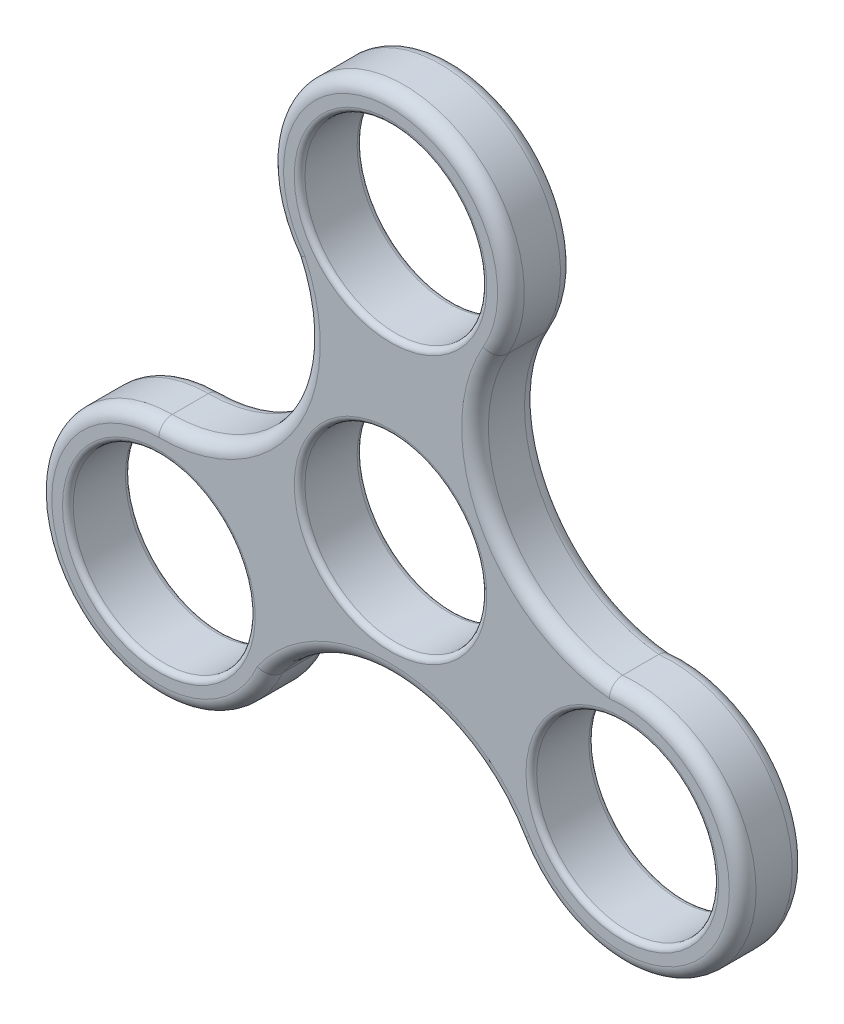
SolidWorks part; units mm, degrees
material "AISI 1020"
ref_plane "Front Plane" through (0, 0, 0) normal (0, 0, 1) x (1, 0, 0)
ref_plane "Top Plane" through (0, 0, 0) normal (0, 1, 0) x (1, 0, 0)
ref_plane "Right Plane" through (0, 0, 0) normal (1, 0, 0) x (0, 0, -1)
sketch "Sketch1" plane through (0, 0, 0) normal (0, 0, 1) x (1, 0, 0)
  line L0 (0, 434.2746) -> (0, -347.9459) construction
  line L1 (-480.6623, 0) -> (486.6372, 0) construction
  line L2 (251.1474, -145) -> (95.2628, -55) construction
  line L3 (-251.1474, -145) -> (-95.2628, -55) construction
  line L4 (-58.8897, -34) -> (58.8897, 34) construction
  line L5 (58.8897, -34) -> (-58.8897, 34) construction
  line L6 (376.0928, -217.1373) -> (-301.33, 173.9729) construction
  line L7 (-376.0928, -217.1373) -> (301.33, 173.9729) construction
  circle A0 centre (0, 0) radius 68
  arc A1 (77.9423, 155) -> (-72.6038, 146.8146) centre (0, 200) ccw
  arc A2 (95.2628, -145) -> (163.447, -10.5306) centre (173.2051, -100) ccw
  arc A3 (-173.2051, -10) -> (-90.8432, -136.284) centre (-173.2051, -100) ccw
  arc A4 (163.447, -10.5306) -> (77.9423, 155) centre (173.7911, 99.6617) cw
  arc A5 (-90.8432, -136.284) -> (95.2628, -145) centre (-0.586, -200.3383) cw
  arc A6 (-72.6038, 146.8146) -> (-173.2051, -10) centre (-173.2051, 100.6767) cw
  circle A7 centre (-173.2051, -100) radius 68
  circle A8 centre (173.2051, -100) radius 68
  circle A9 centre (0, 200) radius 68
  point P19 (0, 0)
  point P37 (0, 0)
  dimension "D1" = 136
  dimension "D2" = 180
  dimension "D4" = 3
  dimension "D5" = 136
  dimension "D3" = 200
  dimension "D6" = 3
extrude "Boss-Extrude1" add sketch "Sketch1" along normal blind 47
fillet "Fillet1" radius 10 12 edges at (-248.5893, -149.1652, 47) (75.4584, 48.8679, 47) (4.5917, -89.7828, 47) (-80.0501, 40.9149, 47) (-4.8862, 289.8673, 47) (-248.5893, -149.1652, 0) (4.5917, -89.7828, 0) (253.4755, -140.702, 0) (253.4755, -140.702, 47) (75.4584, 48.8679, 0) (-4.8862, 289.8673, 0) (-80.0501, 40.9149, 0)
fillet "Fillet2" radius 4 8 edges at (-105.2051, -100, 0) (-105.2051, -100, 47) (241.2051, -100, 0) (241.2051, -100, 47) (68, 0, 0) (68, 0, 47) (68, 200, 47) (68, 200, 0)
